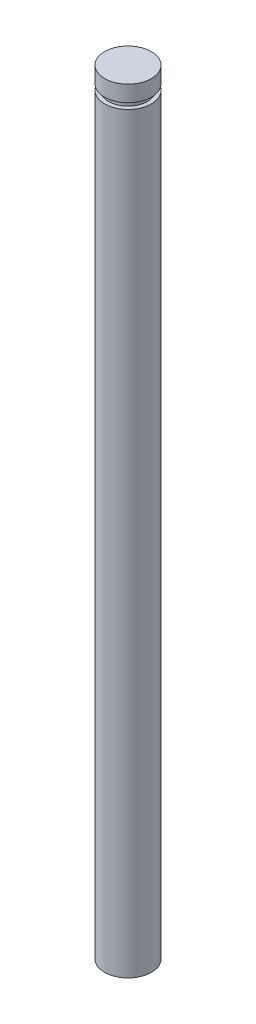
SolidWorks part; units mm, degrees
ref_plane "Front Plane" through (0, 0, 0) normal (0, 0, 1) x (1, 0, 0)
ref_plane "Top Plane" through (0, 0, 0) normal (0, 1, 0) x (1, 0, 0)
ref_plane "Right Plane" through (0, 0, 0) normal (1, 0, 0) x (0, 0, -1)
sketch "Sketch1" plane through (0, 0, 0) normal (0, 0, 1) x (1, 0, 0)
  line L0 (0, 0) -> (0.725, 0)
  line L1 (0.725, 0) -> (0.725, 23.32)
  line L2 (0.725, 23.32) -> (0.6, 23.32)
  line L3 (0.6, 23.32) -> (0.6, 23.5)
  line L4 (0.6, 23.5) -> (0.725, 23.5)
  line L5 (0.725, 23.5) -> (0.725, 24)
  line L6 (0.725, 24) -> (0, 24)
  line L7 (0, 24) -> (0, 0)
  line L8 (0, 0) -> (0, 0.087)
  dimension "D1" = 0.725
  dimension "D2" = 0.6
  dimension "D3" = 0.725
  dimension "D4" = 0.5
  dimension "D5" = 0.18
  dimension "D6" = 24
revolve "Revolve1" add sketch "Sketch1" angle 360 about L7
